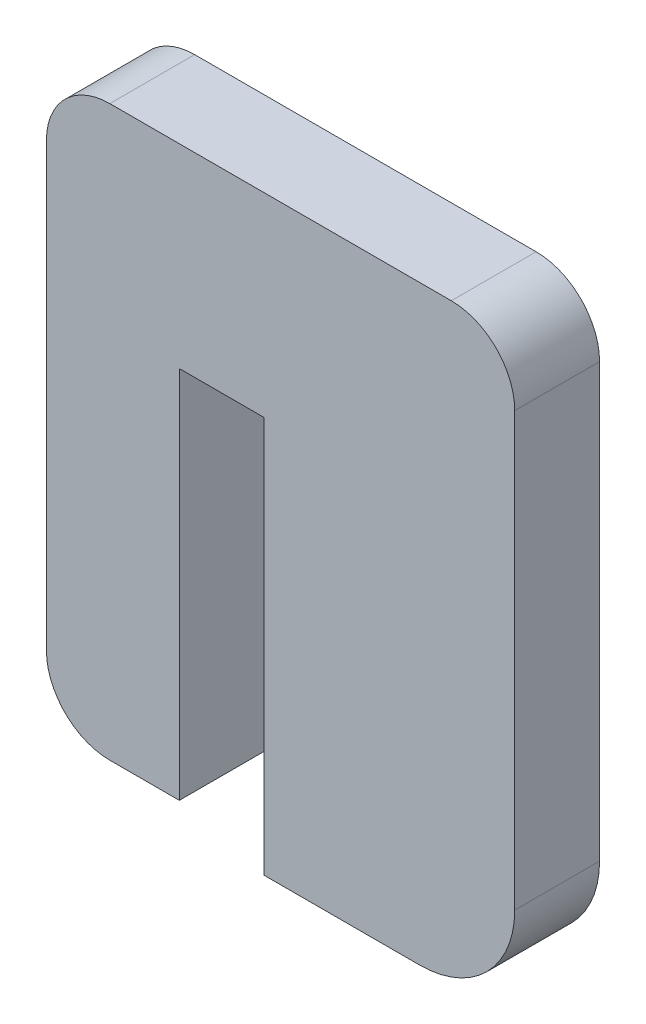
SolidWorks part; units mm, degrees
ref_plane "Front Plane" through (0, 0, 0) normal (0, 0, 1) x (1, 0, 0)
ref_plane "Top Plane" through (0, 0, 0) normal (0, 1, 0) x (1, 0, 0)
ref_plane "Right Plane" through (0, 0, 0) normal (1, 0, 0) x (0, 0, -1)
sketch "Model" plane through (0, 0, 0) normal (0, 0, 1) x (1, 0, 0)
  line L296 (23.5303, 0) -> (13.7303, 0)
  line L297 (29.5303, 33.2782) -> (29.5303, 6)
  line L298 (4, 37.2781) -> (25.5303, 37.2781)
  line L299 (0, 5.4182) -> (0, 33.2781)
  line L300 (8.3803, 1.4182) -> (4, 1.4182)
  line L301 (8.3803, 25) -> (8.3803, 1.4182)
  line L302 (13.7303, 25) -> (8.3803, 25)
  line L303 (13.7303, 0) -> (13.7303, 25)
  arc A26 (0, 5.4182) -> (4, 1.4182) centre (4, 5.4182) ccw
  arc A27 (29.5303, 33.2782) -> (25.5303, 37.2781) centre (25.5303, 33.2781) ccw
  arc A28 (23.5303, 0) -> (29.5303, 6) centre (23.5303, 6) ccw
  arc A29 (4, 37.2781) -> (0, 33.2781) centre (4, 33.2781) ccw
extrude "Boss-Extrude1" add sketch "Model" along normal blind 5.35
